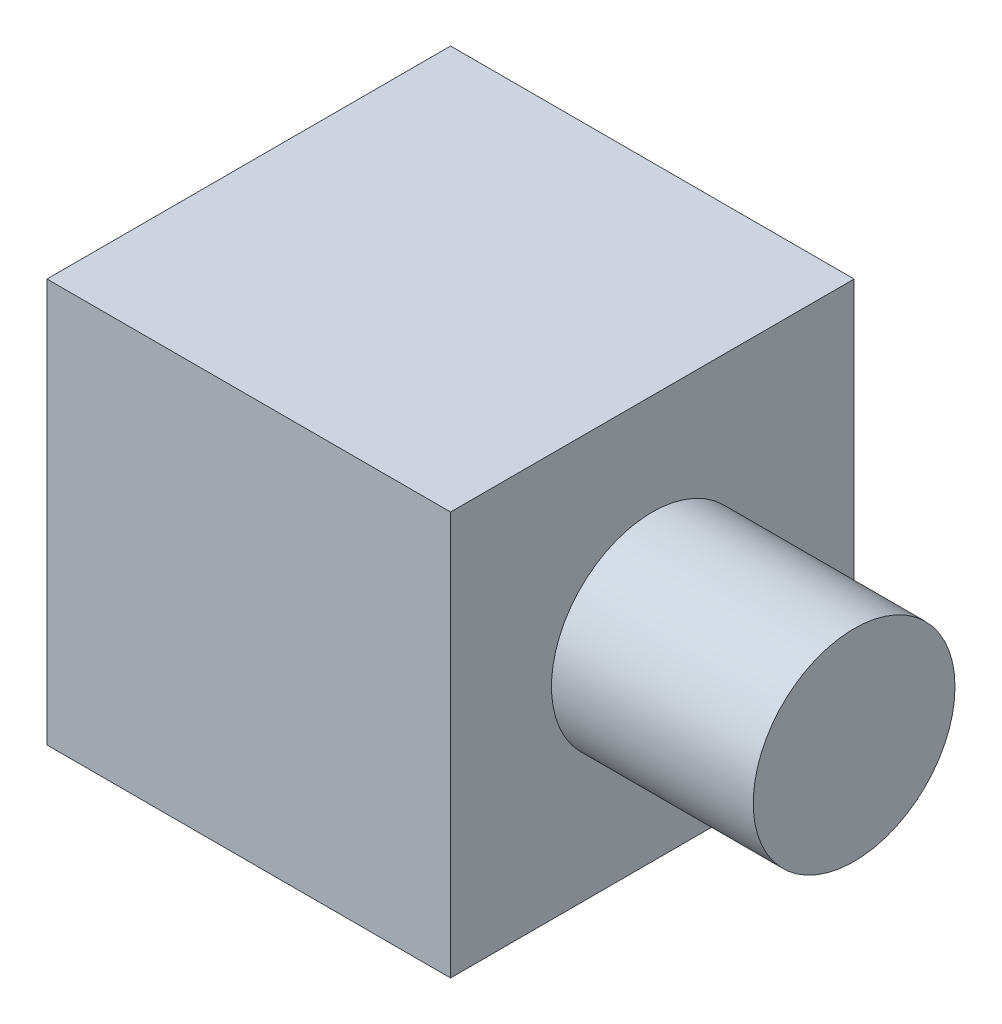
SolidWorks part; units mm, degrees
other "细节项目7"
other "细节项目8"
ref_plane "前视基准面" through (0, 0, 0) normal (0, 0, 1) x (1, 0, 0)
ref_plane "上视基准面" through (0, 0, 0) normal (0, 1, 0) x (1, 0, 0)
ref_plane "右视基准面" through (0, 0, 0) normal (1, 0, 0) x (0, 0, -1)
sketch "草图1" plane through (0, 0, 0) normal (0, 0, 1) x (1, 0, 0)
  line L1 (-10, -10) -> (10, -10)
  line L2 (-10, -10) -> (-10, 10)
  line L3 (-10, 10) -> (10, 10)
  line L4 (10, -10) -> (10, 10)
  line L5 (-10, -10) -> (10, 10) construction
  line L6 (-10, 10) -> (10, -10) construction
  point P0 (0, 0)
extrude "凸台-拉伸1" add sketch "草图1" along normal mid plane 20
sketch "草图2" plane through (10, 0, 0) normal (1, 0, 0) x (0, 0, -1)
  circle A0 centre (0, 0) radius 5
extrude "凸台-拉伸2" add sketch "草图2" along normal blind 10
